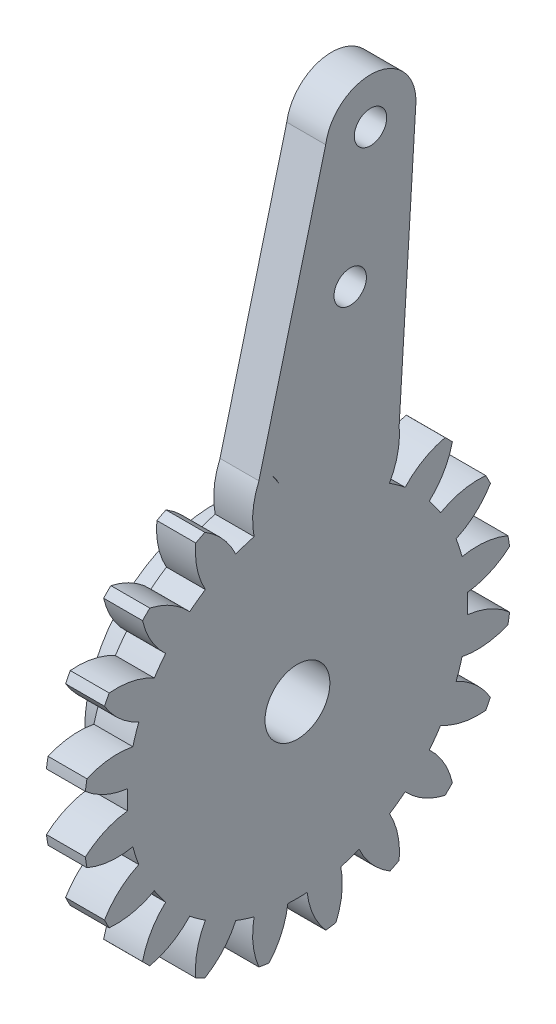
SolidWorks part; units mm, degrees
ref_plane "Plane1" through (0, 0, 0) normal (0, 0, 1) x (1, 0, 0)
ref_plane "Plane2" through (0, 0, 0) normal (0, 1, 0) x (1, 0, 0)
ref_plane "Plane3" through (0, 0, 0) normal (1, 0, 0) x (0, 0, -1)
sketch "HoldingSke" plane through (0, 0, 0) normal (0, 1, 0) x (1, 0, 0)
  line L0 (0, 0) -> (0.6265, -0.228)
  line L1 (-15, 0) -> (100, 0) construction
  line L2 (0, 0) -> (-2.1039, 2.3779)
  line L3 (0, 0) -> (-11.863, 4.5341)
  line L4 (0, 0) -> (8.1152, 2.9537)
  line L5 (0, 0) -> (-46.8476, -17.4728)
  line L6 (0, 0) -> (-2.4869, -1.6779)
  line L7 (-2.1039, 2.3779) -> (8.6586, 51.2059)
  line L8 (-76.2, 54.61) -> (-75.3, 54.61)
  line L9 (-71.009, 38.7566) -> (-53.1078, 45.2721)
  line L10 (-76.2, 71.12) -> (104.1128, 71.12)
  line L11 (0, 0) -> (-3, 0)
  line L12 (-76.2, 101.6) -> (-76.147, 101.6)
  line L13 (24.9733, 27.94) -> (52.9518, 28.4284)
  line L14 (24.9733, 27.94) -> (24.9743, 27.94)
  line L15 (24.9733, 27.94) -> (100.4006, 29.5858)
  line L16 (-63.627, -1.5) -> (-12.827, -1.5)
  circle A0 centre (0, 0) radius 2.5
  circle A1 centre (0, 0) radius 13.124
  circle A2 centre (0, 0) radius 37.5
  circle A3 centre (0, 0) radius 2.5
  dimension "MHD" = 26.248
  dimension "Hub_dia" = 75
  dimension "Bore" = 5
  dimension "MBD" = 5
  dimension "Num_teeth" = 20
  dimension "Pitch" = 0.6667
  dimension "Overall_len" = 50
  dimension "Show_teeth" = 20
  dimension "Thickness" = 3
  dimension "OAL" = 50.0001
  dimension "T_dim" = 0.9
  dimension "Ap" = 20
  dimension "H" = 19.05
  dimension "Pitch_radius" = 180.3128
  dimension "Width" = 3
  dimension "Backlash" = 0.053
  dimension "Addendum_fac" = 1
  dimension "Dedendum_fac" = 1.25
  dimension "Clearance_fac" = 0.25
  dimension "Dedendum_add" = 0.001
  dimension "Module" = 1.5
sketch "BasProSke" plane through (0, 0, 0) normal (0, 1, 0) x (1, 0, 0)
  line L0 (-10, 0) -> (60, 0) construction
  line L1 (0, 0) -> (0, 16.5)
  line L2 (0, 0) -> (3, 0)
  line L3 (3, 0) -> (3, 16.5)
  line L4 (3, 16.5) -> (0, 16.5)
  dimension "Thickness" = 3
  dimension "Diameter" = 33
revolve "Base-Revolve" add sketch "BasProSke" angle 360 about L0
sketch "TooCutSke" plane through (0, 0, 0) normal (1, 0, 0) x (0, 0, -1)
  line L1 (0, 0) -> (0, 107) construction
  line L2 (0, 0) -> (-1.2696, 14.9462) construction
  line L3 (0, 0) -> (-4.6808, 29.5532) construction
  line L4 (-1.2696, 14.9462) -> (-2.3404, 14.7766) construction
  arc A0 (0.7438, 13.1029) -> (-0.7438, 13.1029) centre (0, 0) ccw
  arc A1 (2.21, 16.377) -> (-2.21, 16.377) centre (0, 0) ccw
  circle A2 centre (0, 0) radius 15 construction
  circle A3 centre (0, 0) radius 14.0954 construction
  arc A4 (-0.7438, 13.1029) -> (-2.21, 16.377) centre (-6.7025, 12.3999) ccw
  arc A5 (2.21, 16.377) -> (0.7438, 13.1029) centre (6.7025, 12.3999) ccw
  point P11 (0, 0)
  dimension "Root_dia" = 26.248
  dimension "Overcut_dia" = 33.0508
  dimension "Pitch_dia" = 30
  dimension "Base_dia" = 28.1908
  dimension "Flank_rad" = 6
  dimension "Half_ang" = 9
  dimension "Half_CT" = 1.0841
extrude "ToothCut" cut sketch "TooCutSke" along normal through all
fillet "Breaks" [suppressed] radius 0.03
fillet "RootFillets" [suppressed] radius 0.376
pattern_circular "TeethCuts" count 20 every 18 about axis through (-10, 0, 0) along (1, 0, 0) of "ToothCut", "RootFillets", "Breaks"
sketch "HubNeaOneSke" plane through (0, 0, 0) normal (-1, 0, 0) x (0, 0, 1)
  circle A0 centre (0, 0) radius 13.124
  dimension "Diameter" = 26.248
extrude "HubNearOne" [suppressed] add sketch "HubNeaOneSke" along normal blind 47.0001
sketch "HubNeaBotSke" plane through (0, 0, 0) normal (-1, 0, 0) x (0, 0, 1)
  circle A0 centre (0, 0) radius 13.124
  dimension "Diameter" = 26.248
extrude "HubNearBoth" [suppressed] add sketch "HubNeaBotSke" along normal blind 23.5
ref_plane "FarPln" through (3, 0, 0) normal (1, 0, 0) x (0, 0, -1)
sketch "HubFarSke" plane through (3, 0, 0) normal (1, 0, 0) x (0, 0, -1)
  circle A0 centre (0, 0) radius 13.124
  dimension "Diameter" = 26.248
extrude "HubFar" [suppressed] add sketch "HubFarSke" along normal blind 23.5
sketch "BorSke" plane through (0, 0, 0) normal (1, 0, 0) x (0, 0, -1)
  circle A0 centre (0, 0) radius 2.5
  dimension "Diameter" = 5
extrude "Bore" [suppressed] cut sketch "BorSke" along normal mid plane 100.0001
sketch "KeySke" plane through (0, 0, 0) normal (1, 0, 0) x (0, 0, -1)
  line L0 (-1, 0) -> (-1, 3.4)
  line L1 (-1, 3.4) -> (1, 3.4)
  line L2 (1, 3.4) -> (1, 0)
  line L3 (0, 0) -> (0, 34) construction
  line L4 (-1, 0) -> (1, 0)
  dimension "Offset" = 3.4
  dimension "Width" = 2
extrude "Keyway" [suppressed] cut sketch "KeySke" along normal mid plane 100.0001
pattern_circular "Keyway2" [suppressed] count 2 every 90 about axis through (-10, 0, 0) along (1, 0, 0)
sketch "草图2" plane through (0, 0, 0) normal (-1, 0, 0) x (0, 0, 1)
  line L0 (0, 0) -> (-5.6316, 35.5568) construction
  line L2 (-3.4569, -0.5475) -> (-9.0885, 35.0093)
  line L3 (3.4569, 0.5475) -> (-2.1747, 36.1043)
  arc A0 (-3.4569, -0.5475) -> (3.4569, 0.5475) centre (0, 0) ccw
  arc A1 (-2.1747, 36.1043) -> (-9.0885, 35.0093) centre (-5.6316, 35.5568) ccw
  circle A2 centre (-4.0673, 25.6799) radius 1.25
  circle A3 centre (-5.6316, 35.5568) radius 1.25
  point P5 (-2.8158, 17.7784)
  dimension "D1" = 3.5
  dimension "D3" = 10
  dimension "D2" = 36
sketch "草图3" plane through (0, 0, 0) normal (-1, 0, 0) x (0, 0, 1)
  line L0 (0, 0) -> (0, 107) construction
  circle A0 centre (0, 0) radius 2.5
  circle A1 centre (0, 27) radius 2.5
  dimension "D1" = 27
  dimension "D2" = 5
  dimension "D3" = 5
extrude "切除-拉伸2" cut sketch "草图3" against normal blind 10
sketch "草图4" plane through (0, 0, 0) normal (-1, 0, 0) x (0, 0, 1)
  circle A0 centre (0, 0) radius 10
extrude "凸台-拉伸4" add sketch "草图4" along normal blind 3.4
sketch "草图6" plane through (-3.4, 0, 0) normal (-1, 0, 0) x (0, 0, 1)
  circle A0 centre (0, 0) radius 2.5
extrude "切除-拉伸3" cut sketch "草图6" against normal through all
extrude "凸台-拉伸5" add sketch "草图2" against normal blind 3
sketch "草图7" plane through (3, 0, 0) normal (1, 0, 0) x (0, 0, -1)
  circle A0 centre (0, 0) radius 2.5
extrude "切除-拉伸4" cut sketch "草图7" against normal through all
sketch "草图8" plane through (0, 0, 0) normal (-1, 0, 0) x (0, 0, 1)
  line L0 (-7.8411, 14.5178) -> (-9.125, 35.3414)
  line L1 (2.9711, 16.2303) -> (-2.1747, 36.1043)
  line L2 (-9.125, 35.3414) -> (-5.7132, 13.6984)
  line L3 (-7.8411, 14.5178) -> (-7.1363, 14.8769)
  line L4 (-7.1363, 14.8769) -> (-5.7132, 13.6984)
  arc A0 (-2.1747, 36.1043) -> (-9.0885, 35.0093) centre (-5.6316, 35.5568) ccw construction
extrude "凸台-拉伸6" add sketch "草图8" against normal up to surface (3 mm away) contours L3 L4 L2 L0
sketch "草图9" plane through (0, 0, 0) normal (-1, 0, 0) x (0, 0, 1)
  line L0 (2.9711, 16.2303) -> (-2.1747, 36.1043)
  line L4 (1.2006, 14.7934) -> (-2.1747, 36.1043) construction
  line L5 (1.2006, 14.7934) -> (-2.1747, 36.1043)
  line L6 (2.1898, 16.354) -> (1.6486, 15.6897)
  line L7 (1.6486, 15.6897) -> (1.3038, 15.0213)
  line L8 (1.3038, 15.0213) -> (1.2006, 14.7934)
  arc A0 (2.9711, 16.2303) -> (2.1898, 16.354) centre (0, 0) ccw construction
  arc A2 (2.9711, 16.2303) -> (2.1898, 16.354) centre (0, 0) ccw
extrude "凸台-拉伸14" add sketch "草图9" against normal blind 3
equation "' \"Module@HoldingSke\" = 6.35"
equation "' \"Num_teeth@HoldingSke\" = 12"
equation "' \"Ap@HoldingSke\" =  20"
equation "' \"Ap@HoldingSke\" = 20"
equation "' \"Width@HoldingSke\" = 0.5 * 25.4"
equation "' \"Hub_dia@HoldingSke\"= 1 * 25.4"
equation "' \"Hub_dia@HoldingSke\" = 1 * 25.4"
equation "' \"Overall_len@HoldingSke\" = 1.0 * 25.4"
equation "' \"Bore@HoldingSke\" = 0.75 * 25.4"
equation "' \"T_dim@HoldingSke\" = 0.1 * 25.4"
equation "' \"Width@KeySke\" = 0.25 * 25.4"
equation "' \"Show_teeth@HoldingSke\" = 13"
equation "' \"Backlash@HoldingSke\" = 0.009 * 25.4"
equation "' \"Addendum_fac@HoldingSke\" = 1.0"
equation "' \"Dedendum_fac@HoldingSke\" = 1.25"
equation "' \"Dedendum_add@HoldingSke\" = 0.00005 * 25.4"
equation "' \"Clearance_fac@HoldingSke\" = 0.25"
equation "\"Pitch@HoldingSke\" = 1 / \"Module@HoldingSke\""
equation "\"Overcut_dia@TooCutSke\" = (\"Num_teeth@HoldingSke\" + 2 * \"Addendum_fac@HoldingSke\") / \"Pitch@HoldingSke\" + 0.002 * 25.4"
equation "\"Pitch_dia@TooCutSke\" = \"Num_teeth@HoldingSke\" / \"Pitch@HoldingSke\""
equation "\"Base_dia@TooCutSke\" = \"Num_teeth@HoldingSke\" / \"Pitch@HoldingSke\" * cos((\"Ap@HoldingSke\"  * 3.14159265 / 180))"
equation "\"Root_dia@TooCutSke\" = (\"Num_teeth@HoldingSke\" + 2) / \"Pitch@HoldingSke\" - 2 * (\"Addendum_fac@HoldingSke\" + \"Dedendum_fac@HoldingSke\") / \"Pitch@HoldingSke\" - \"Dedendum_add@HoldingSke\" * 2"
equation "\"Half_ang@TooCutSke\" = 180 / \"Num_teeth@HoldingSke\""
equation "\"Half_CT@TooCutSke\" = \"Num_teeth@HoldingSke\" / \"Pitch@HoldingSke\" * sin((3.14159265 / 2 / \"Num_teeth@HoldingSke\")) / 2 - 7 * \"Backlash@HoldingSke\" / 4"
equation "\"Flank_rad@TooCutSke\" = \"Num_teeth@HoldingSke\" / \"Pitch@HoldingSke\" / 5"
equation "\"Radius@RootFillets\" = \"Clearance_fac@HoldingSke\" / \"Pitch@HoldingSke\" + \"Dedendum_add@HoldingSke\""
equation "\"Break_rad@Breaks\" = 0.02 / \"Pitch@HoldingSke\""
equation "\"Thickness@HoldingSke\" = \"Width@HoldingSke\""
equation "\"OAL@HoldingSke\" = \"Thickness@HoldingSke\""
equation "\"MHD@HoldingSke\" = (\"Num_teeth@HoldingSke\" + 2) / \"Pitch@HoldingSke\" - 2 * (\"Addendum_fac@HoldingSke\" + \"Dedendum_fac@HoldingSke\")  / \"Pitch@HoldingSke\" - \"Dedendum_add@HoldingSke\" * 2"
equation "\"MBD@HoldingSke\" = (\"Num_teeth@HoldingSke\" + 2) / \"Pitch@HoldingSke\" - 2 * (\"Addendum_fac@HoldingSke\" + \"Dedendum_fac@HoldingSke\")  / \"Pitch@HoldingSke\" - \"Dedendum_add@HoldingSke\" * 2 - 0.002 * 25.4"
equation "\"MHD@HoldingSke\" = ((sgn( \"MHD@HoldingSke\" - \"Hub_dia@HoldingSke\" )-1)*( \"MHD@HoldingSke\" - \"Hub_dia@HoldingSke\" ))/-2+ \"Hub_dia@HoldingSke\""
equation "\"MBD@HoldingSke\" = ((sgn( \"MBD@HoldingSke\" - \"Bore@HoldingSke\" )-1)*( \"MBD@HoldingSke\" - \"Bore@HoldingSke\" ))/-2+ \"Bore@HoldingSke\""
equation "\"OAL@HoldingSke\" = ((sgn( \"OAL@HoldingSke\" - \"Overall_len@HoldingSke\" )+1)*( \"OAL@HoldingSke\" - \"Overall_len@HoldingSke\" ))/2 + \"Overall_len@HoldingSke\" + 0.000002 * 25.4"
equation "\"Num_teeth@TeethCuts\" = int( \"Show_teeth@HoldingSke\" ) + 1"
equation "\"Num_teeth@TeethCuts\" = ((sgn( \"Num_teeth@TeethCuts\" - \"Num_teeth@HoldingSke\" )-1)*( \"Num_teeth@TeethCuts\" - \"Num_teeth@HoldingSke\" ))/-2+ \"Num_teeth@HoldingSke\""
equation "\"Num_teeth@TeethCuts\" = ((sgn( \"Num_teeth@TeethCuts\" - 2.0)+1)*( \"Num_teeth@TeethCuts\" - 2.0))/2 +2.0"
equation "\"Angle@TeethCuts\" = 360.0 / \"Num_teeth@HoldingSke\""
equation "\"Diameter@BasProSke\" = (\"Num_teeth@HoldingSke\" + 2 * \"Addendum_fac@HoldingSke\") / \"Pitch@HoldingSke\""
equation "\"Thickness@BasProSke\"  = \"Thickness@HoldingSke\""
equation "' \"Fillet_rad@BasProSke\" =  \"Thickness@HoldingSke\" * 0.05"
equation "' \"Fillet_rad@BasProSke\" = \"Thickness@HoldingSke\" * 0.05"
equation "\"MHD@HoldingSke\" = ((sgn( \"MHD@HoldingSke\" - \"Root_dia@TooCutSke\" )-1)*( \"MHD@HoldingSke\" - \"Root_dia@TooCutSke\" ))/-2+ \"Root_dia@TooCutSke\""
equation "\"Diameter@HubNeaOneSke\" = \"MHD@HoldingSke\""
equation "\"Length@HubNearOne\" = \"OAL@HoldingSke\" - \"Thickness@BasProSke\""
equation "\"Diameter@HubNeaBotSke\" = \"MHD@HoldingSke\""
equation "\"Length@HubNearBoth\" = ( \"OAL@HoldingSke\" - \"Thickness@BasProSke\" ) / 2.0"
equation "\"Thickness@FarPln\" = \"Thickness@BasProSke\""
equation "\"Diameter@HubFarSke\" = \"MHD@HoldingSke\""
equation "\"Length@HubFar\" = ( \"OAL@HoldingSke\" - \"Thickness@BasProSke\" ) / 2.0"
equation "\"Diameter@BorSke\" = \"MBD@HoldingSke\""
equation "\"D1@Bore\" = \"OAL@HoldingSke\" * 2.0"
equation "\"D1@Keyway\" = \"OAL@HoldingSke\" * 2.0"
equation "\"Offset@KeySke\" = \"T_dim@HoldingSke\" + \"MBD@HoldingSke\" / 2.0"
